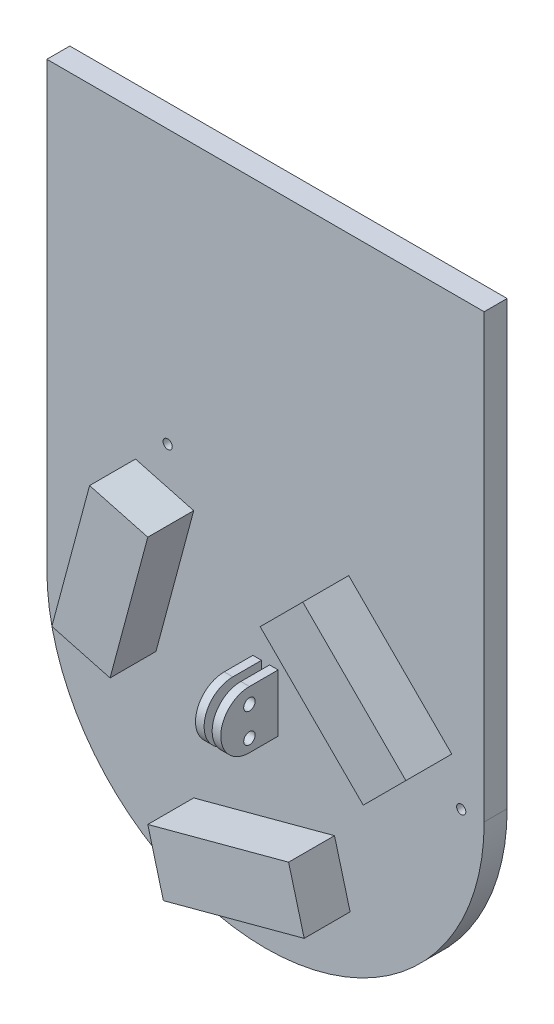
SolidWorks part; units mm, degrees
ref_plane "Front Plane" through (0, 0, 0) normal (0, 0, 1) x (1, 0, 0)
ref_plane "Top Plane" through (0, 0, 0) normal (0, 1, 0) x (1, 0, 0)
ref_plane "Right Plane" through (0, 0, 0) normal (1, 0, 0) x (0, 0, -1)
sketch "Sketch2" plane through (0, 0, 0) normal (0, 0, 1) x (1, 0, 0)
  circle A0 centre (0, 0) radius 38.1
  point P11 (0, 0)
  dimension "D1" = 76.2
extrude "Boss-Extrude1" add sketch "Sketch2" along normal blind 4 contours A0
sketch "Sketch11" plane through (0, 0, 0) normal (0, 0, -1) x (-1, 0, 0)
  line L0 (-38.1, 0) -> (38.1, 0)
  line L1 (-38.1, 0) -> (-38.1, 77)
  line L2 (38.1, 0) -> (38.1, 77)
  line L3 (-38.1, 77) -> (38.1, 77)
  circle A0 centre (0, 0) radius 38.1 construction
  dimension "D1" = 77
extrude "Boss-Extrude4" add sketch "Sketch11" against normal blind 4
sketch "Sketch3" plane through (0, 0, 4) normal (0, 0, 1) x (1, 0, 0)
  circle A0 centre (34.1, -0.0857) radius 0.8
  circle A1 centre (-17.05, -29.6172) radius 0.8
  circle A2 centre (-17.05, 29.4457) radius 0.8
  point P8 (0, -0.0857)
  dimension "D1" = 1.6
  dimension "D3" = 34.1
  dimension "D2" = 3
extrude "Cut-Extrude1" cut sketch "Sketch3" against normal blind 6
sketch "Sketch4" plane through (0, 0, 4) normal (0, 0, 1) x (1, 0, 0)
  circle A0 centre (0, 0) radius 0.6
  dimension "D1" = 1.2
extrude "Cut-Extrude2" cut sketch "Sketch4" against normal blind 6
sketch "Sketch5" plane through (0, 0, 4) normal (0, 0, 1) x (1, 0, 0)
  line L1 (0.7, 5) -> (2.2, 5)
  line L2 (0.7, 5) -> (0.7, -5)
  line L3 (0.7, -5) -> (2.2, -5)
  line L4 (2.2, 5) -> (2.2, -5)
  line L5 (-0.7, 5) -> (-2.2, 5)
  line L6 (-0.7, 5) -> (-0.7, -5)
  line L7 (-0.7, -5) -> (-2.2, -5)
  line L8 (-2.2, 5) -> (-2.2, -5)
  dimension "D1" = 10
  dimension "D2" = 1.5
  dimension "D3" = 2.2
  dimension "D4" = 5
  dimension "D5" = 2.2
  dimension "D6" = 5
extrude "Boss-Extrude2" add sketch "Sketch5" along normal blind 10
sketch "Sketch6" plane through (2.2, 0, 0) normal (1, 0, 0) x (0, 0, -1)
  line L0 (-14, -5) -> (-4, -5) construction
  line L1 (-14, 5) -> (-4, 5) construction
  line L2 (-9, 5) -> (-14, 5)
  line L3 (-14, 5) -> (-14, -5)
  line L5 (-14, -5) -> (-9, -5)
  line L6 (-14, 5) -> (-9, 5)
  arc A2 (-9, -5) -> (-9, 5) centre (-9, 0) cw
  point P1 (-9, -5)
  point P2 (-9.1485, 5)
  line M5 (-4, 5) -> (-14, 5)
  line M6 (-14, 5) -> (-14, -5)
  line M7 (-14, -5) -> (-4, -5)
extrude "Cut-Extrude3" cut sketch "Sketch6" against normal through all contours A2 M6 M5 | A2 L3 M7
sketch "Sketch7" plane through (2.2, 0, 0) normal (1, 0, 0) x (0, 0, -1)
  line L1 (-9, 5) -> (-4, 5) construction
  line L2 (-9, -5) -> (-4, -5) construction
  circle A2 centre (-9, 2.3) radius 1
  circle A3 centre (-9, -2.8) radius 1
  dimension "D1" = 2.7
  dimension "D2" = 2.2
  dimension "D4" = 2
extrude "Cut-Extrude4" cut sketch "Sketch7" against normal through all
sketch "Sketch8" plane through (0, 0, 4) normal (0, 0, 1) x (1, 0, 0)
  line L0 (25.0288, 0) -> (32.4534, 7.4246)
  line L1 (25.0288, 0) -> (7.0683, 17.9605)
  line L2 (32.4534, 7.4246) -> (14.4929, 25.3851)
  line L3 (7.0683, 17.9605) -> (14.4929, 25.3851)
  line L4 (0, 0) -> (50000, 0) construction
  line L5 (12.0201, -15.1016) -> (14.7377, -25.2438)
  line L6 (-9.7968, -31.8178) -> (14.7377, -25.2438)
  line L7 (-12.5144, -21.6756) -> (-9.7968, -31.8178)
  line L8 (-12.5144, -21.6756) -> (12.0201, -15.1016)
  line L9 (-19.0884, -2.8589) -> (-29.2306, -0.1413)
  line L10 (-22.6566, 24.3932) -> (-29.2306, -0.1413)
  line L11 (-12.5144, 21.6756) -> (-22.6566, 24.3932)
  line L12 (-12.5144, 21.6756) -> (-19.0884, -2.8589)
  point P17 (0, 0)
  dimension "D1" = 10.5
  dimension "D2" = 25.4
  dimension "D3" = 45
  dimension "D4" = 25.0288
  dimension "D5" = 3
extrude "Boss-Extrude3" add sketch "Sketch8" along normal blind 8
